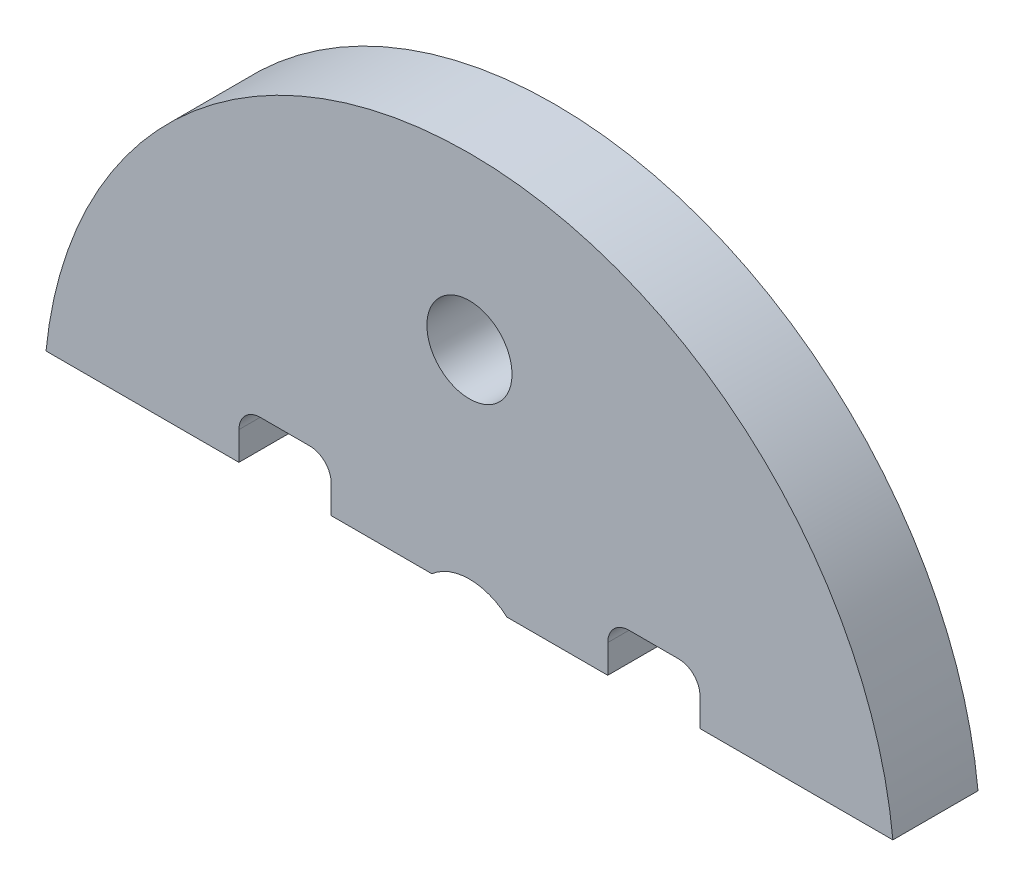
SolidWorks part; units mm, degrees
ref_plane "Alzado" through (0, 0, 0) normal (0, 0, 1) x (1, 0, 0)
ref_plane "Planta" through (0, 0, 0) normal (0, 1, 0) x (1, 0, 0)
ref_plane "Vista lateral" through (0, 0, 0) normal (1, 0, 0) x (0, 0, -1)
sketch "Model" plane through (0, 0, 0) normal (0, 0, 1) x (1, 0, 0)
  line L0 (223.1228, 245.202) -> (221.3728, 245.202)
  line L1 (208.3728, 245.202) -> (210.1228, 245.202)
  line L2 (223.8728, 243.452) -> (230.6726, 243.452)
  line L3 (223.8728, 243.452) -> (223.8728, 244.452)
  line L4 (220.6228, 244.452) -> (220.6228, 243.452)
  line L5 (210.8728, 244.452) -> (210.8728, 243.452)
  line L6 (207.6228, 243.452) -> (207.6228, 244.452)
  line L7 (200.823, 243.452) -> (207.6228, 243.452)
  line L8 (210.8728, 243.452) -> (214.4249, 243.452)
  line L9 (217.0707, 243.452) -> (220.6228, 243.452)
  circle A0 centre (215.7478, 250.952) radius 1.5
  arc A1 (221.3728, 245.202) -> (220.6228, 244.452) centre (221.3728, 244.452) ccw
  arc A2 (223.8728, 244.452) -> (223.1228, 245.202) centre (223.1228, 244.452) ccw
  arc A3 (210.8728, 244.452) -> (210.1228, 245.202) centre (210.1228, 244.452) ccw
  arc A4 (208.3728, 245.202) -> (207.6228, 244.452) centre (208.3728, 244.452) ccw
  arc A5 (217.0707, 243.452) -> (214.4249, 243.452) centre (215.7478, 241.952) ccw
  arc A6 (230.6726, 243.452) -> (200.823, 243.452) centre (215.7478, 241.952) ccw
extrude "Saliente-Extruir1" add sketch "Model" along normal blind 3
